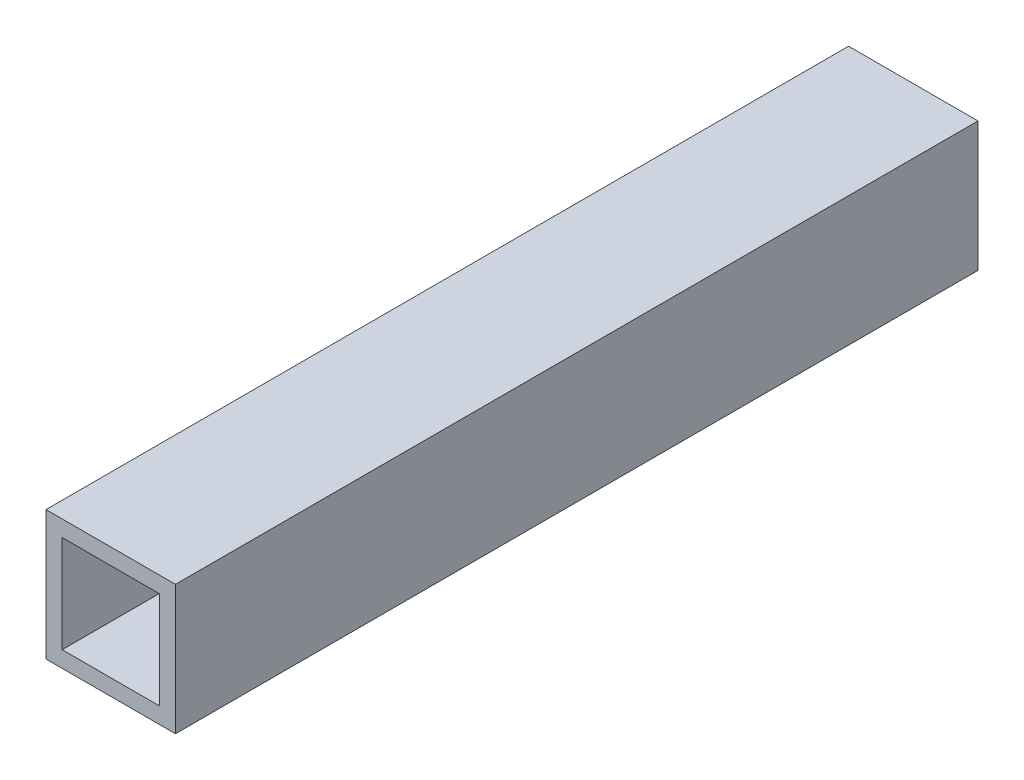
SolidWorks part; units mm, degrees
material "6061 Alloy"
ref_plane "Front Plane" through (0, 0, 0) normal (0, 0, 1) x (1, 0, 0)
ref_plane "Top Plane" through (0, 0, 0) normal (0, 1, 0) x (1, 0, 0)
ref_plane "Right Plane" through (0, 0, 0) normal (1, 0, 0) x (0, 0, -1)
sketch "Sketch1" plane through (0, 0, 0) normal (0, 0, 1) x (1, 0, 0)
  line L0 (12.7, 0) -> (9.525, 0) construction
  line L1 (-12.7, 0) -> (12.7, 0) construction
  line L2 (0, 12.7) -> (0, -12.7)
  point P7 (0, 0)
sketch "Sketch2" plane through (0, 0, 0) normal (1, 0, 0) x (0, 0, -1)
  line L0 (78.74, 0) -> (-78.74, 0)
  point P4 (0, 0)
  dimension "Length" = 157.48
sketch "Sketch3" plane through (0, 0, 0) normal (0, 0, 1) x (1, 0, 0)
  line L0 (-12.7, 0) -> (12.7, 0) construction
  line L5 (12.7, -12.7) -> (-12.7, -12.7)
  line L6 (12.7, -12.7) -> (12.7, 12.7)
  line L11 (12.7, 12.7) -> (-12.7, 12.7)
  line L12 (-12.7, -12.7) -> (-12.7, 12.7)
  line L14 (12.7, -12.7) -> (-12.7, 12.7) construction
  line L15 (12.7, 12.7) -> (-12.7, -12.7) construction
  line L16 (9.525, -9.525) -> (-9.525, -9.525)
  line L17 (9.525, -9.525) -> (9.525, 9.525)
  line L18 (9.525, 9.525) -> (-9.525, 9.525)
  line L19 (-9.525, -9.525) -> (-9.525, 9.525)
  line L20 (9.525, -9.525) -> (-9.525, 9.525) construction
  line L21 (9.525, 9.525) -> (-9.525, -9.525) construction
  point P0 (0, 0)
  point P5 (0, 0)
  point P13 (9.525, -12.7)
  dimension "D1" = 3.175
  dimension "D3" = 25.4
  dimension "D4" = 25.4
extrude "Boss-Extrude1" add sketch "Sketch3" along normal up to vertex (78.74 mm away) and the other way up to vertex (78.74 mm away) up to point (0, 0, 78.74) other way up to point (0, 0, -78.74)
sketch "Sketch5" plane through (0, 0, 0) normal (1, 0, 0) x (0, 0, -1)
  line L0 (-78.74, 0) -> (78.74, 0) construction
  line L3 (-78.74, -12.7) -> (-78.74, 12.7) construction
  line L4 (78.74, -12.7) -> (78.74, 12.7) construction
  point P6 (-50.165, 0)
  point P7 (-40.64, 0)
  point P8 (40.64, 0)
  point P10 (50.165, 0)
  dimension "D1" = 28.575
  dimension "D2" = 38.1
  dimension "D3" = 28.575
  dimension "D4" = 38.1
equation "\"D1@Sketch3\"=\"Wall thickness@Sketch1\""
equation "\"D1@Sketch5\"=\"Width@Sketch1\"*1.125"
equation "\"D2@Sketch5\"=\"Width@Sketch1\"*1.5"
equation "\"D3@Sketch5\"=\"D1@Sketch5\""
equation "\"D4@Sketch5\"=\"D2@Sketch5\""
equation "\"D2@Sketch3\"=\"Wall Thickness@Sketch1\""
